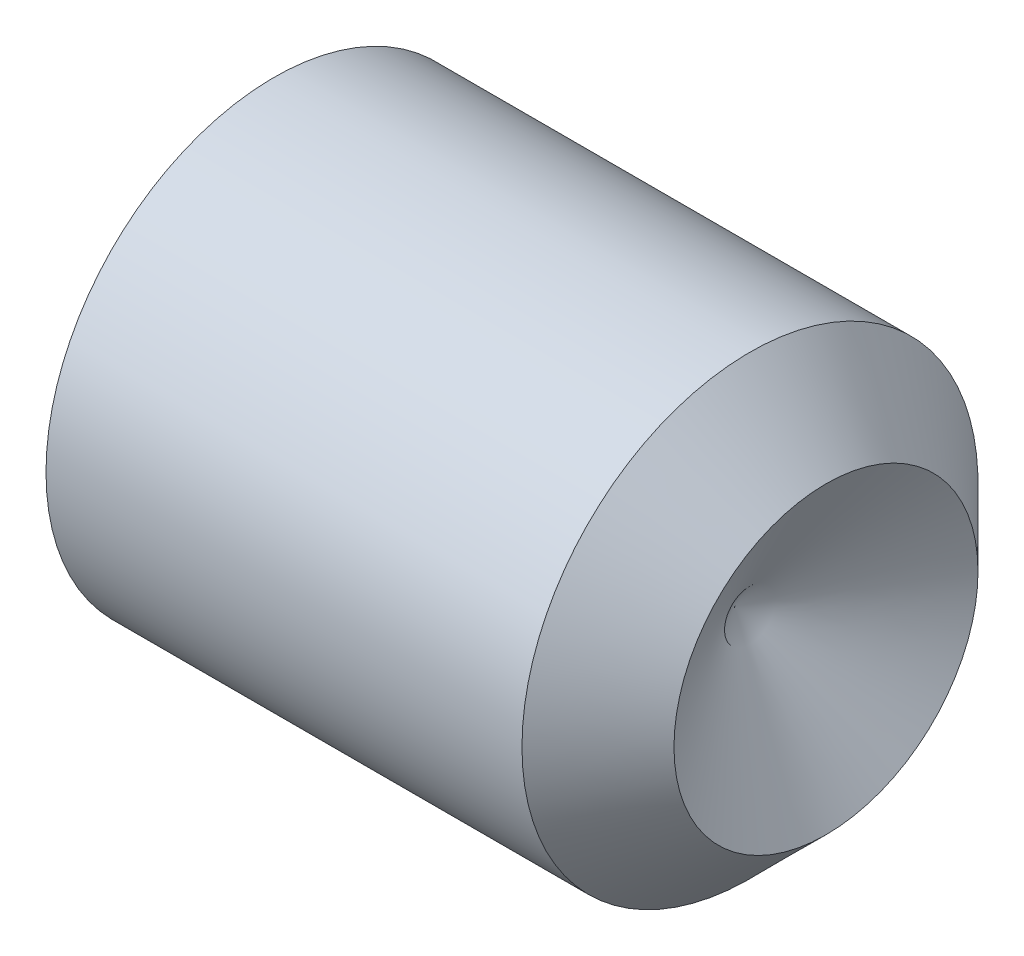
SolidWorks part; units mm, degrees
revolve "BaseBody" add sketch "BodySke" angle 360 about L5
sketch "BodySke" plane through (0, 0, 0) normal (0, 0, 1) x (1, 0, 0)
  line L0 (0, 0) -> (0, 10.352)
  line L1 (0, 10.352) -> (0.9515, 12)
  line L2 (0.9515, 12) -> (26, 12)
  line L3 (26, 12) -> (30, 8)
  line L4 (25.1931, 0) -> (0, 0)
  line L5 (-12.7, 0) -> (88.9, 0) construction
  line L6 (25.1931, 0) -> (30, 8)
  line L7 (30, 8) -> (30, 17.525) construction
  line L8 (0, -10.352) -> (0.9515, -12) construction
  line L9 (25.1931, 0) -> (30, -8) construction
  line L10 (26, -12) -> (30, -8) construction
  line L11 (3, 15.875) -> (3, -3.175) construction
  dimension "Diameter" = 24
  dimension "Drive_ch_ang" = 60
  dimension "Minor_dia" = 20.704
  dimension "Cup_nose_ang" = 45
  dimension "Cup_ang" = 118
  dimension "Cup_dia" = 16
  dimension "Length" = 30
  dimension "Advance" = 3
cosmetic thread "ThreadCosmetic" [suppressed] parameters "Thread_minor"=20.704
ref_plane "Plane1" through (0, 0, 0) normal (0, 0, 1) x (1, 0, 0)
ref_plane "Plane2" through (0, 0, 0) normal (0, 1, 0) x (1, 0, 0)
ref_plane "Plane3" through (0, 0, 0) normal (1, 0, 0) x (0, 0, -1)
sketch "Sketch2" plane through (0, 0, 0) normal (-1, 0, 0) x (0, 0, 1)
  line L0 (3.4641, 6) -> (-3.4641, 6)
  line L1 (-3.4641, 6) -> (-6.9282, 0)
  line L2 (3.4641, 6) -> (6.9282, 0)
  line L3 (3.4641, -6) -> (6.9282, 0)
  line L4 (3.4641, -6) -> (-3.4641, -6)
  line L5 (-3.4641, -6) -> (-6.9282, 0)
  dimension "Hex_size" = 12
  dimension "D2" = 6
  dimension "D3" = 6
extrude "Hex" [suppressed] cut sketch "Sketch2" against normal blind 12
sketch "Sketch4" plane through (0, 4.7709, -0.5249) normal (-1, 0, 0) x (0, 0, 1)
  line L0 (0.5249, -4.7709) -> (8.1959, -4.7709)
  line L1 (0.5249, -4.7709) -> (6.6732, -1.2211) construction
  line L2 (0.5249, -4.7709) -> (4.3604, 1.8724)
  line L3 (6.7899, -3.1774) -> (7.8687, -2.5545)
  line L4 (5.0374, -0.142) -> (6.1162, 0.4809)
  arc A0 (6.7899, -3.1774) -> (5.0374, -0.142) centre (0.5249, -4.7709) ccw
  arc A1 (8.1959, -4.7709) -> (7.8687, -2.5545) centre (0.5249, -4.7709) ccw
  arc A2 (4.3604, 1.8724) -> (6.1162, 0.4809) centre (0.5249, -4.7709) cw
  circle A3 centre (0.5249, -4.7709) radius 6.4645 construction
  circle A4 centre (0.5249, -4.7709) radius 7.671 construction
  dimension "Spline_n_dim" = 12.929
  dimension "Spline_m_dim" = 15.342
  dimension "D1" = 30
  dimension "Spline_a_dim" = 60
  dimension "Spline_p_dim" = 3.505
  dimension "D3" = 1.7525
extrude "Spline6" [suppressed] cut sketch "Sketch4" against normal blind 12
pattern_circular "CirPattern1" [suppressed] count 6 every 60 about axis through (-12.7, 0, 0) along (1, 0, 0)
sketch "Sketch5" plane through (0, 1.5227, 6.1981) normal (-1, 0, 0) x (0, 0, 1)
  line L0 (-6.1981, -1.5227) -> (1.4729, -1.5227)
  line L1 (-6.1981, -1.5227) -> (-1.178, 3.4975) construction
  line L2 (-6.1981, -1.5227) -> (-6.1981, 6.1483)
  line L3 (-0.3878, 1.8092) -> (0.3219, 2.5189)
  line L4 (-2.8662, 4.2876) -> (-2.1565, 4.9973)
  line L5 (-2.8662, 4.2876) -> (-0.3878, 1.8092)
  arc A1 (1.4729, -1.5227) -> (0.3219, 2.5189) centre (-6.1981, -1.5227) ccw
  arc A2 (-6.1981, 6.1483) -> (-2.1565, 4.9973) centre (-6.1981, -1.5227) cw
  circle A3 centre (-6.1981, -1.5227) radius 6.4645 construction
  circle A4 centre (-6.1981, -1.5227) radius 7.671 construction
  dimension "Spline_n_dim" = 12.929
  dimension "Spline_m_dim" = 15.342
  dimension "Spline_p_dim" = 3.505
  dimension "D3" = 1.7525
  dimension "D1" = 45
  dimension "Spline_a_dim" = 90
extrude "Spline4" cut sketch "Sketch5" against normal blind 12
pattern_circular "CirPattern2" count 4 every 90 about axis through (0, 0, 0) along (1, 0, 0) of "Spline4"
sketch "ThdSchSke" plane through (0, 0, 0) normal (0, 0, 1) x (1, 0, 0)
  line L0 (0.9515, -10.352) -> (-0.2025, -12)
  line L1 (0.9515, -10.352) -> (2.1054, -12)
  line L2 (2.1054, -12) -> (2.1054, -15)
  line L3 (-3.175, 0) -> (5.1513, 0) construction
  line L4 (0.9515, 12) -> (0.9515, -12) construction
  line L5 (2.1054, -15) -> (-0.2025, -15)
  line L6 (-0.2025, -15) -> (-0.2025, -12)
  dimension "Thread_minor" = 20.704
  dimension "Diameter" = 24
revolve "ThreadSchematic" [suppressed] cut sketch "ThdSchSke" angle 360 about L3
pattern_linear "ThdSchPat" [suppressed]
equation "\"D2@Sketch2\" = \"Hex_size@Sketch2\" / 2"
equation "\"D3@Sketch2\" = \"Hex_size@Sketch2\" / 2"
equation "\"Thread_minor@ThreadCosmetic\" = \"Minor_dia@BodySke\""
equation "\"D1@Sketch4\" = \"Spline_a_dim@Sketch4\" / 2"
equation "\"D3@Sketch4\" = \"Spline_p_dim@Sketch4\" / 2"
equation "\"D2@CirPattern1\" = \"Spline_a_dim@Sketch4\""
equation "\"Num_teeth@CirPattern1\" = 360 / \"D2@CirPattern1\""
equation "\"Spline_a_dim@Sketch5\" = 90"
equation "\"Spline_p_dim@Sketch5\" = \"Spline_p_dim@Sketch4\""
equation "\"Spline_m_dim@Sketch5\" = \"Spline_m_dim@Sketch4\""
equation "\"Spline_n_dim@Sketch5\" = \"Spline_n_dim@Sketch4\""
equation "\"D1@Sketch5\" = \"Spline_a_dim@Sketch5\" / 2"
equation "\"D3@Sketch5\" = \"Spline_p_dim@Sketch5\" / 2"
equation "\"Key_eng@Spline4\" = \"Key_eng@Spline6\""
equation "\"Thread_minor@ThdSchSke\" = \"Thread_minor@ThreadCosmetic\""
equation "\"Diameter@ThdSchSke\" = \"Diameter@BodySke\""
equation "\"Overcut@ThdSchSke\" = \"Diameter@BodySke\" * 1.25"
equation "\"Num_threads@ThdSchPat\" = int( (\"Length@BodySke\" - ( ( ( \"Diameter@BodySke\" - \"Minor_dia@BodySke\" ) * 0.5 ) / tan( \"Drive_ch_ang@BodySke\" * 0.017453292 ) ) - ( ( ( \"Diameter@BodySke\" - \"Cup_dia@BodySke\" ) * 0.5 ) * tan( \"Cup_nose_ang@BodySke\" * 0.017453292 ) ) ) / \"Advance@BodySke\" + 0.999 )  + 1"
equation "\"Advance@ThdSchPat\" = (\"Length@BodySke\" - ( ( ( \"Diameter@BodySke\" - \"Minor_dia@BodySke\" ) * 0.5 ) / tan( \"Drive_ch_ang@BodySke\" * 0.017453292 ) ) - ( ( ( \"Diameter@BodySke\" - \"Cup_dia@BodySke\" ) * 0.5 ) * tan( \"Cup_nose_ang@BodySke\" * 0.017453292 ) ) ) /  (\"Num_threads@ThdSchPat\" - 1) 'relax it"
equation "' \"Num_threads@ThdSchPat\" = \"Num_threads@ThdSchPat\" - sgn( \"Num_threads@ThdSchPat\" - 1) '---chamfered tips only---"
